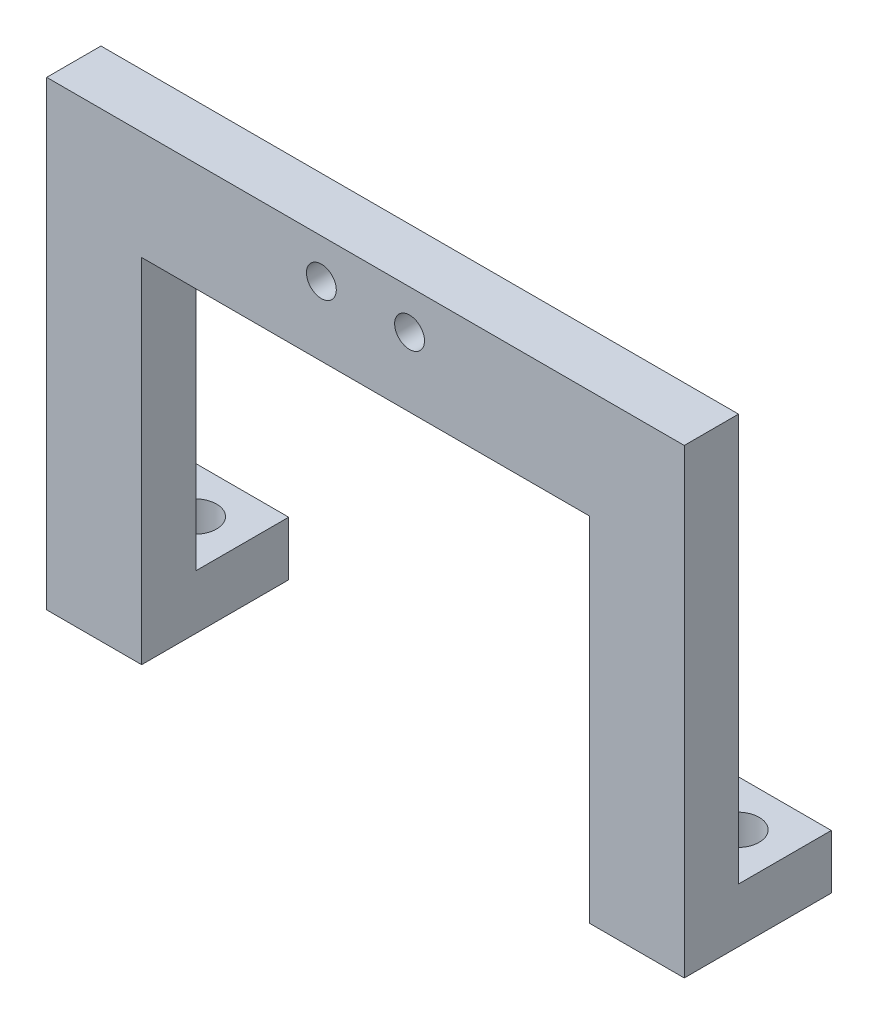
SolidWorks part; units mm, degrees
ref_plane "前视基准面" through (0, 0, 0) normal (0, 0, 1) x (1, 0, 0)
ref_plane "上视基准面" through (0, 0, 0) normal (0, 1, 0) x (1, 0, 0)
ref_plane "右视基准面" through (0, 0, 0) normal (1, 0, 0) x (0, 0, -1)
sketch "草图2" plane through (0, 0, 0) normal (0, 1, 0) x (1, 0, 0)
  line L0 (0, 10) -> (0, -10) construction
  line L1 (-20, -10) -> (20, -10) construction
  line L2 (-20, -10) -> (-20, 10) construction
  line L3 (-20, 10) -> (20, 10) construction
  line L4 (20, -10) -> (20, 10) construction
  line L5 (-20, -10) -> (20, 10) construction
  line L6 (-20, 10) -> (20, -10) construction
  line L7 (-23.5, 3.4199) -> (-16.5, 3.4199)
  line L8 (-23.5, -3.4199) -> (-16.5, -3.4199) construction
  line L9 (-23.5, -3.4199) -> (-23.5, 3.4199) construction
  line L10 (-23.5, 3.4199) -> (-16.5, 3.4199) construction
  line L11 (-16.5, -3.4199) -> (-16.5, 3.4199) construction
  line L12 (-23.5, -3.4199) -> (-16.5, 3.4199) construction
  line L13 (-23.5, 3.4199) -> (-16.5, -3.4199) construction
  line L14 (-6.5, -2.9) -> (6.5, -2.9) construction
  line L15 (-6.5, -2.9) -> (-6.5, 2.9) construction
  line L16 (-6.5, 2.9) -> (6.5, 2.9) construction
  line L17 (6.5, -2.9) -> (6.5, 2.9) construction
  line L18 (-6.5, -2.9) -> (6.5, 2.9) construction
  line L19 (-6.5, 2.9) -> (6.5, -2.9) construction
  line L20 (-16.5, 3.4199) -> (-16.5, -3.4199)
  line L21 (-16.5, -3.4199) -> (-16.5, -7.4199)
  line L22 (-16.5, -7.4199) -> (-23.5, -7.4199)
  line L23 (-23.5, -7.4199) -> (-23.5, -3.4199)
  line L24 (-23.5, -3.4199) -> (-23.5, 3.4199)
  line L25 (23.5, -7.4199) -> (23.5, -3.4199)
  line L26 (16.5, -7.4199) -> (23.5, -7.4199)
  line L27 (16.5, -3.4199) -> (16.5, -7.4199)
  line L28 (16.5, 3.4199) -> (16.5, -3.4199)
  line L29 (23.5, 3.4199) -> (16.5, 3.4199)
  line L30 (23.5, -3.4199) -> (23.5, 3.4199)
  circle A0 centre (-20, 0) radius 1.6
  circle A1 centre (20, 0) radius 1.6
  point P0 (0, 0)
  point P15 (0, 0)
  dimension "D3" = 3.2
  dimension "D1" = 40
  dimension "D2" = 20
  dimension "D4" = 5.8
  dimension "D5" = 13
  dimension "D6" = 7
  dimension "D7" = 4
extrude "凸台-拉伸1" add sketch "草图2" along normal blind 4
sketch "草图3" plane through (0, 4, 0) normal (0, 1, 0) x (1, 0, 0)
  line L1 (-23.5, -3.4199) -> (-16.5, -3.4199)
  line L2 (-23.5, -3.4199) -> (-23.5, -7.4199)
  line L3 (-23.5, -7.4199) -> (-16.5, -7.4199)
  line L4 (-16.5, -3.4199) -> (-16.5, -7.4199)
  line L5 (16.5, -3.4199) -> (23.5, -3.4199)
  line L6 (16.5, -3.4199) -> (16.5, -7.4199)
  line L7 (16.5, -7.4199) -> (23.5, -7.4199)
  line L8 (23.5, -3.4199) -> (23.5, -7.4199)
extrude "凸台-拉伸2" add sketch "草图3" along normal blind 30
sketch "草图4" plane through (0, 0, 3.4199) normal (0, 0, -1) x (-1, 0, 0)
  line L0 (23.5, 34) -> (23.5, 4) construction
  line L1 (-23.5, 34) -> (23.5, 34)
  line L2 (-23.5, 34) -> (-23.5, 26)
  line L3 (-23.5, 26) -> (23.5, 26)
  line L4 (23.5, 34) -> (23.5, 26)
  dimension "D1" = 8
extrude "凸台-拉伸3" add sketch "草图4" against normal blind 4
sketch "草图5" plane through (0, 0, 3.4199) normal (0, 0, -1) x (-1, 0, 0)
  line L0 (0, 34) -> (0, 26) construction
  line L1 (-23.5, 34) -> (23.5, 34) construction
  line L2 (-16.5, 26) -> (16.5, 26) construction
  circle A0 centre (-3.25, 31.1) radius 1.1
  circle A2 centre (3.25, 31.1) radius 1.1
  dimension "D2" = 5.1
  dimension "D1" = 6.5
  dimension "D3" = 2.2
extrude "切除-拉伸1" cut sketch "草图5" against normal through all
